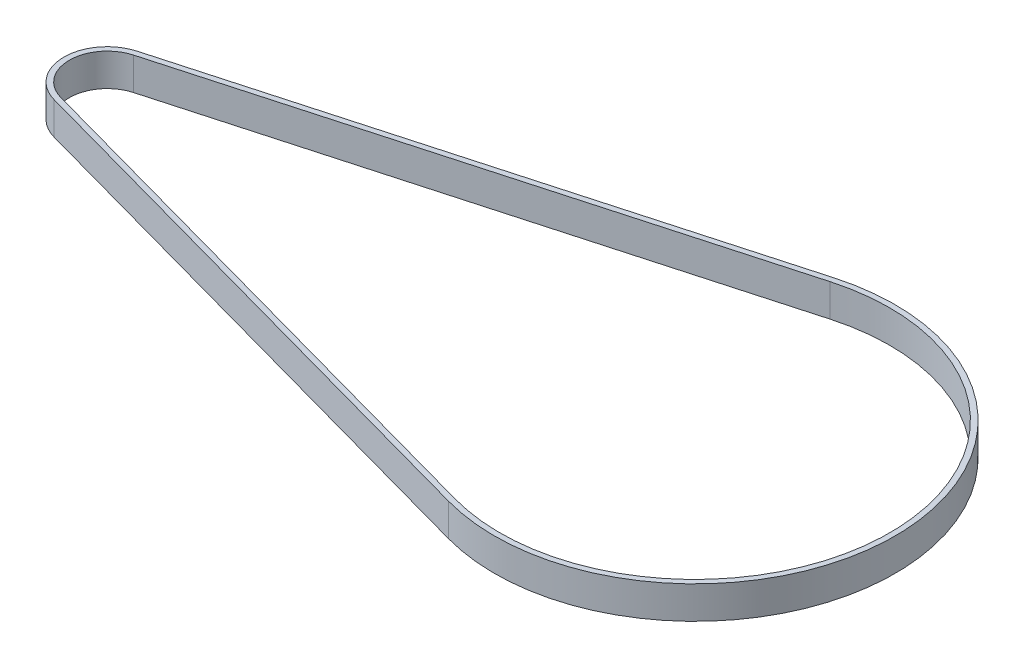
SolidWorks part; units mm, degrees
ref_plane "Front Plane" through (0, 0, 0) normal (0, 0, 1) x (1, 0, 0)
ref_plane "Top Plane" through (0, 0, 0) normal (0, 1, 0) x (1, 0, 0)
ref_plane "Right Plane" through (0, 0, 0) normal (1, 0, 0) x (0, 0, -1)
sketch "Sketch1" plane through (0, 0, 0) normal (0, 1, 0) x (1, 0, 0)
  line L0 (1.808, -7.6504) -> (102.447, -35.4533)
  line L1 (1.7867, 7.766) -> (102.3483, 35.8474)
  line L2 (2.0743, -6.6865) -> (102.7133, -34.4894)
  line L3 (2.0556, 6.8029) -> (102.6172, 34.8843)
  arc A3 (1.7867, 7.766) -> (1.808, -7.6504) centre (3.9383, 0.0608) ccw
  circle A4 centre (112.2997, 0.2108) radius 37 construction
  arc A5 (102.447, -35.4533) -> (102.3483, 35.8474) centre (112.2997, 0.2108) ccw
  arc A6 (102.7133, -34.4894) -> (102.6172, 34.8843) centre (112.2997, 0.2108) ccw
  arc A7 (2.0556, 6.8029) -> (2.0743, -6.6865) centre (3.9383, 0.0608) ccw
  dimension "D1" = 1
extrude "Boss-Extrude1" add sketch "Sketch1" along normal blind 6
